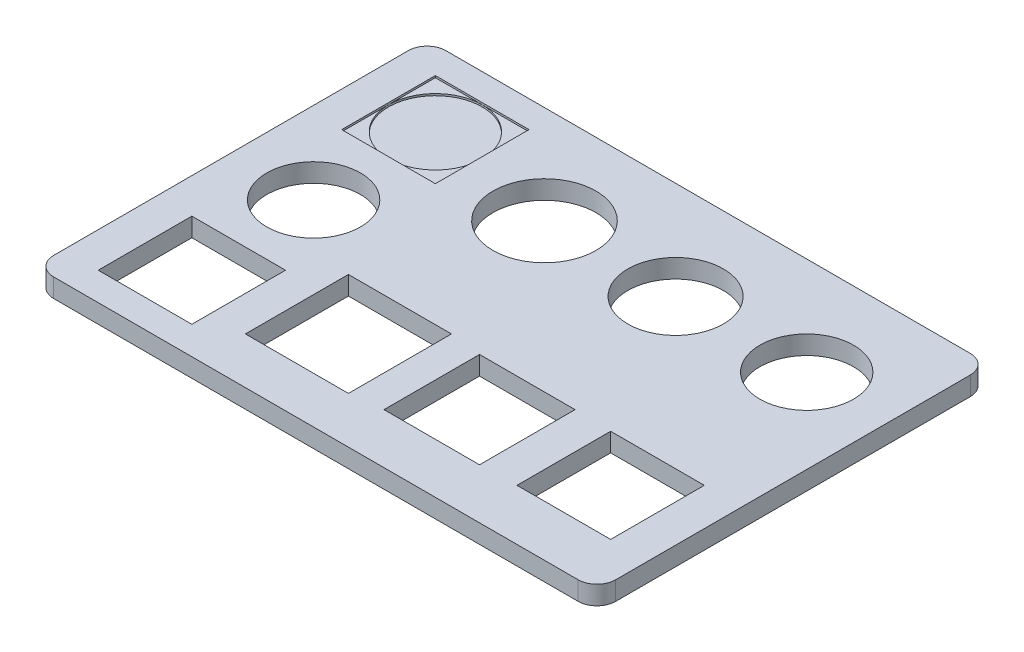
SolidWorks part; units mm, degrees
ref_plane "Front Plane" through (0, 0, 0) normal (0, 0, 1) x (1, 0, 0)
ref_plane "Top Plane" through (0, 0, 0) normal (0, 1, 0) x (1, 0, 0)
ref_plane "Right Plane" through (0, 0, 0) normal (1, 0, 0) x (0, 0, -1)
sketch "Sketch1" plane through (0, 0, 0) normal (0, 1, 0) x (1, 0, 0)
  line L0 (0, 104.666) -> (300, 104.666) construction
  line L1 (0, 0) -> (300, 0)
  line L2 (0, 0) -> (0, 209.332)
  line L3 (0, 209.332) -> (300, 209.332)
  line L4 (300, 0) -> (300, 209.332)
  line L5 (45, 209.332) -> (45, 104.666) construction
  line L6 (45, 104.666) -> (45, 0) construction
  line L7 (45, 156.999) -> (300, 156.999) construction
  line L8 (45, 52.333) -> (300, 52.333) construction
  line L9 (20, 156.999) -> (0, 156.999) construction
  line L10 (115, 209.332) -> (115, 0) construction
  line L11 (185, 209.332) -> (185, 0) construction
  line L12 (87.5, 24.833) -> (142.5, 24.833)
  line L13 (87.5, 24.833) -> (87.5, 79.833)
  line L14 (87.5, 79.833) -> (142.5, 79.833)
  line L15 (142.5, 24.833) -> (142.5, 79.833)
  line L16 (87.5, 24.833) -> (142.5, 79.833) construction
  line L17 (87.5, 79.833) -> (142.5, 24.833) construction
  line L18 (255, 209.332) -> (255, 0) construction
  line L20 (159.5, 26.833) -> (210.5, 26.833)
  line L21 (159.5, 26.833) -> (159.5, 77.833)
  line L22 (159.5, 77.833) -> (210.5, 77.833)
  line L23 (210.5, 26.833) -> (210.5, 77.833)
  line L24 (159.5, 26.833) -> (210.5, 77.833) construction
  line L25 (159.5, 77.833) -> (210.5, 26.833) construction
  line L26 (280, 27.333) -> (230, 27.333)
  line L27 (280, 27.333) -> (280, 77.333)
  line L28 (280, 77.333) -> (230, 77.333)
  line L29 (230, 27.333) -> (230, 77.333)
  line L30 (280, 27.333) -> (230, 77.333) construction
  line L31 (280, 77.333) -> (230, 27.333) construction
  circle A0 centre (45, 156.999) radius 25
  circle A1 centre (45, 52.333) radius 25
  circle A2 centre (115, 156.999) radius 27.5
  circle A3 centre (185, 156.999) radius 25.5
  circle A4 centre (255, 156.999) radius 25
  point P22 (115, 52.333)
  point P35 (185, 52.333)
  point P40 (255, 52.333)
  point P45 (185, 135)
  point P46 (255, 135)
  point P47 (255, 135)
  point P48 (255, 45)
  point P49 (255, 45)
  point P50 (255, 45)
  point P51 (172.5, 45)
  point P52 (0, 0)
  point P53 (0, 0)
  point P54 (0, 0)
  point P55 (185, 45)
  point P56 (185, 45)
  dimension "D1" = 50
  dimension "D2" = 20
  dimension "D3" = 27.333
  dimension "D5" = 55
  dimension "D12" = 50
  dimension "D13" = 51
  dimension "D4" = 70
  dimension "D6" = 55
  dimension "D7" = 70
  dimension "D8" = 70
  dimension "D9" = 20
  dimension "D10" = 50
  dimension "D11" = 51
extrude "Boss-Extrude1" add sketch "Sketch1" along normal blind 10
sketch "Sketch2" plane through (0, 10, 0) normal (0, 1, 0) x (1, 0, 0)
  line L1 (70, 131.999) -> (20, 131.999)
  line L2 (70, 131.999) -> (70, 181.999)
  line L3 (70, 181.999) -> (20, 181.999)
  line L4 (20, 131.999) -> (20, 181.999)
  line L5 (70, 131.999) -> (20, 181.999) construction
  line L6 (70, 181.999) -> (20, 131.999) construction
  point P0 (45, 156.999)
extrude "Cut-Extrude1" cut sketch "Sketch2" against normal blind 1
sketch "Sketch3" plane through (0, 9, 0) normal (0, 1, 0) x (1, 0, 0)
  circle A0 centre (45, 156.999) radius 25
extrude "Boss-Extrude2" add sketch "Sketch3" against normal up to surface (8 mm away) from offset 1 up to face at (185, 0, -131.499) offset against normal yes
sketch "Sketch4" plane through (0, 10, 0) normal (0, 1, 0) x (1, 0, 0)
  line L1 (20, 27.333) -> (70, 27.333)
  line L2 (20, 27.333) -> (20, 77.333)
  line L3 (20, 77.333) -> (70, 77.333)
  line L4 (70, 27.333) -> (70, 77.333)
  line L5 (20, 27.333) -> (70, 77.333) construction
  line L6 (20, 77.333) -> (70, 27.333) construction
  point P0 (45, 52.333)
extrude "Cut-Extrude2" cut sketch "Sketch4" against normal through all
fillet "Fillet1" radius 10 4 edges at (0, 5, 0) (0, 5, -209.332) (300, 5, -209.332) (300, 5, 0)
sketch "Sketch5" plane through (0, 10, 0) normal (0, 1, 0) x (1, 0, 0)
  line L1 (20, 181.999) -> (70, 181.999)
  line L2 (20, 181.999) -> (20, 131.999)
  line L3 (20, 131.999) -> (70, 131.999)
  line L4 (70, 181.999) -> (70, 131.999)
  line L5 (20, 77.333) -> (70, 77.333)
  line L6 (20, 77.333) -> (20, 27.333)
  line L7 (20, 27.333) -> (70, 27.333)
  line L8 (70, 77.333) -> (70, 27.333)
extrude "Boss-Extrude3" add sketch "Sketch5" against normal up to surface (10 mm away) up to face at (45, 0, -52.333)
sketch "Sketch6" plane through (0, 10, 0) normal (0, 1, 0) x (1, 0, 0)
  line L0 (87.5, 156.999) -> (0, 156.999) construction
  line L1 (0, 199.332) -> (0, 10) construction
  line L2 (87.5, 52.333) -> (0, 52.333) construction
  line L3 (87.5, 79.833) -> (87.5, 24.833) construction
  line L4 (43.75, 156.999) -> (43.75, 0) construction
  line L5 (10, 0) -> (290, 0) construction
  line L6 (43.75, 156.999) -> (43.75, 209.332) construction
  line L7 (290, 209.332) -> (10, 209.332) construction
  line L9 (68.75, 15) -> (18.75, 15)
  line L10 (68.75, 15) -> (68.75, 65)
  line L11 (68.75, 65) -> (18.75, 65)
  line L12 (18.75, 15) -> (18.75, 65)
  line L13 (68.75, 15) -> (18.75, 65) construction
  line L14 (68.75, 65) -> (18.75, 15) construction
  line L15 (68.75, 145) -> (18.75, 145)
  line L16 (68.75, 145) -> (68.75, 195)
  line L17 (68.75, 195) -> (18.75, 195)
  line L18 (18.75, 145) -> (18.75, 195)
  line L19 (68.75, 145) -> (18.75, 195) construction
  line L20 (68.75, 195) -> (18.75, 145) construction
  circle A0 centre (115, 156.999) radius 27.5 construction
  circle A1 centre (43.75, 105) radius 25
  point P18 (43.75, 40)
  point P25 (43.75, 170)
  point P30 (43.75, 177.4383)
  dimension "D1" = 50
  dimension "D4" = 15
  dimension "D2" = 50
  dimension "D3" = 15
  dimension "D5" = 50
  dimension "D6" = 15
extrude "Cut-Extrude3" cut sketch "Sketch6" against normal through all
sketch "Sketch7" plane through (0, 10, 0) normal (0, 1, 0) x (1, 0, 0)
  line L1 (18.75, 195) -> (68.75, 195)
  line L2 (18.75, 195) -> (18.75, 145)
  line L3 (18.75, 145) -> (68.75, 145)
  line L4 (68.75, 195) -> (68.75, 145)
extrude "Boss-Extrude4" add sketch "Sketch7" against normal up to surface (9 mm away) from offset 1 up to face at (43.75, 0, -40) offset against normal yes
sketch "Sketch8" plane through (0, 9, 0) normal (0, 1, 0) x (1, 0, 0)
  line L0 (18.75, 195) -> (68.75, 145) construction
  line L1 (18.75, 145) -> (68.75, 145) construction
  line L2 (68.75, 145) -> (68.75, 195) construction
  circle A0 centre (43.75, 170) radius 25
extrude "Cut-Extrude4" cut sketch "Sketch8" against normal blind 1
